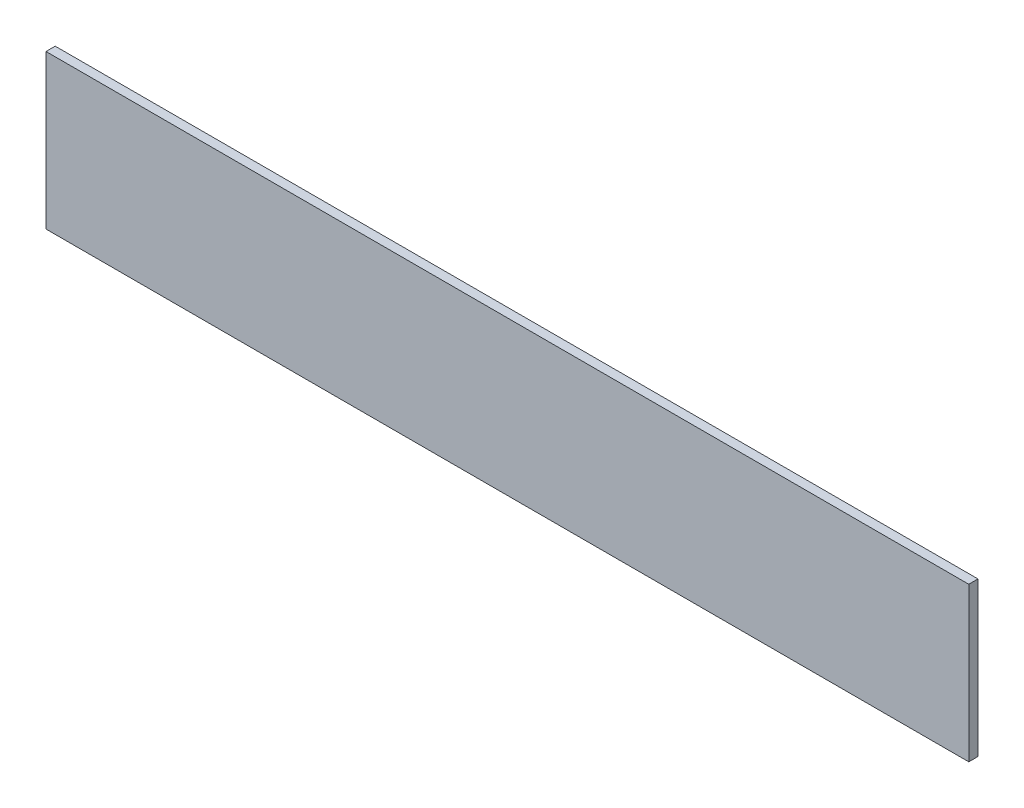
SolidWorks part; units mm, degrees
ref_plane "Front Plane" through (0, 0, 0) normal (0, 0, 1) x (1, 0, 0)
ref_plane "Top Plane" through (0, 0, 0) normal (0, 1, 0) x (1, 0, 0)
ref_plane "Right Plane" through (0, 0, 0) normal (1, 0, 0) x (0, 0, -1)
sketch "Sketch1" plane through (0, 0, 0) normal (0, 0, 1) x (1, 0, 0)
  line L1 (-167.0319, 36.6036) -> (132.9681, 36.6036)
  line L2 (-167.0319, 36.6036) -> (-167.0319, -13.3964)
  line L3 (-167.0319, -13.3964) -> (132.9681, -13.3964)
  line L4 (132.9681, 36.6036) -> (132.9681, -13.3964)
  dimension "D1" = 300
  dimension "D2" = 50
extrude "Boss-Extrude1" add sketch "Sketch1" along normal blind 3 contours L2 L1 L4 L3
